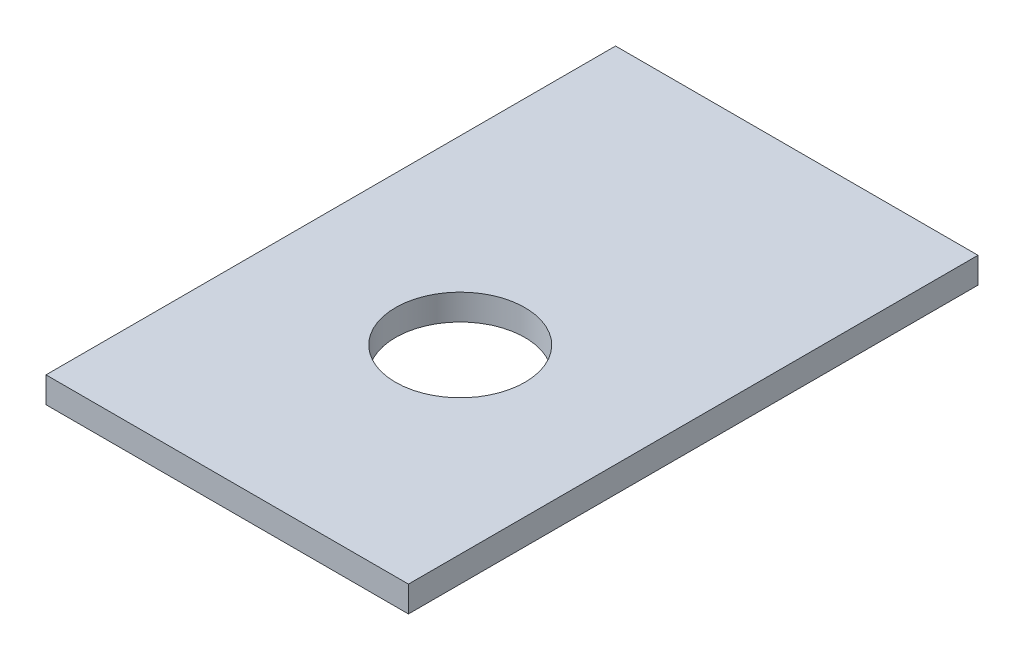
SolidWorks part; units mm, degrees
ref_plane "Alzado" through (0, 0, 0) normal (0, 0, 1) x (1, 0, 0)
ref_plane "Planta" through (0, 0, 0) normal (0, 1, 0) x (1, 0, 0)
ref_plane "Vista lateral" through (0, 0, 0) normal (1, 0, 0) x (0, 0, -1)
sketch "Croquis1" plane through (0, 0, 0) normal (0, 1, 0) x (1, 0, 0)
  line L1 (-29.2038, 18.8376) -> (40.7962, 18.8376)
  line L2 (-29.2038, 18.8376) -> (-29.2038, -91.1624)
  line L3 (-29.2038, -91.1624) -> (40.7962, -91.1624)
  line L4 (40.7962, 18.8376) -> (40.7962, -91.1624)
  circle A0 centre (5.7962, -46.1624) radius 12.5
  dimension "D5" = 25
  dimension "D1" = 70
  dimension "D2" = 110
  dimension "D3" = 65
  dimension "D4" = 35
extrude "Saliente-Extruir1" add sketch "Croquis1" along normal blind 5
